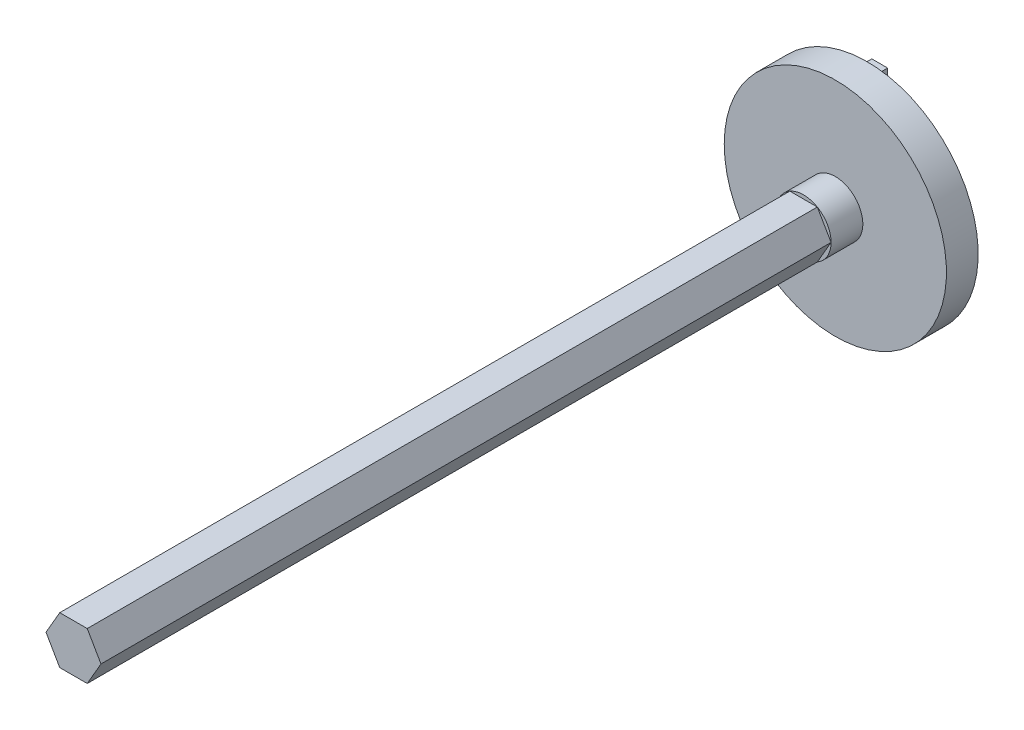
SolidWorks part; units mm, degrees
ref_plane "Front Plane" through (0, 0, 0) normal (0, 0, 1) x (1, 0, 0)
ref_plane "Top Plane" through (0, 0, 0) normal (0, 1, 0) x (1, 0, 0)
ref_plane "Right Plane" through (0, 0, 0) normal (1, 0, 0) x (0, 0, -1)
sketch "Sketch1" plane through (0, 0, 0) normal (0, 0, 1) x (1, 0, 0)
  line L1 (5.4993, 9.525) -> (-5.4993, 9.525)
  line L2 (-5.4993, 9.525) -> (-10.9985, 0)
  line L3 (-10.9985, 0) -> (-5.4993, -9.525)
  line L4 (-5.4993, -9.525) -> (5.4993, -9.525)
  line L5 (5.4993, -9.525) -> (10.9985, 0)
  line L6 (10.9985, 0) -> (5.4993, 9.525)
  circle A0 centre (0, 0) radius 9.525 construction
  point P1 (0, 0)
  point P10 (-5.4606, -0.651)
  dimension "D1" = 19.05
extrude "Boss-Extrude1" add sketch "Sketch1" along normal blind 304.8 contours L2 L3 L4 L5 L6 L1
sketch "Sketch2" plane through (0, 0, 0) normal (0, 0, -1) x (-1, 0, 0)
  circle A0 centre (0, 0) radius 10.9985
extrude "Boss-Extrude2" add sketch "Sketch2" against normal blind 12.7
sketch "Sketch3" plane through (0, 0, 0) normal (0, 0, -1) x (-1, 0, 0)
  circle A0 centre (0, 0) radius 44.45
  dimension "D1" = 88.9
extrude "Boss-Extrude3" add sketch "Sketch3" along normal blind 12.7
sketch "Sketch4" plane through (0, 0, -12.7) normal (0, 0, -1) x (-1, 0, 0)
  line L1 (-3.175, 41.275) -> (3.175, 41.275)
  line L2 (-3.175, 41.275) -> (-3.175, 34.925)
  line L3 (-3.175, 34.925) -> (3.175, 34.925)
  line L4 (3.175, 41.275) -> (3.175, 34.925)
  line L5 (-3.175, 41.275) -> (3.175, 34.925) construction
  line L6 (-3.175, 34.925) -> (3.175, 41.275) construction
  point P0 (0, 38.1)
  point P5 (0, 0)
  dimension "D1" = 6.35
  dimension "D2" = 6.35
  dimension "D3" = 38.1
extrude "Boss-Extrude4" add sketch "Sketch4" along normal blind 5.08
